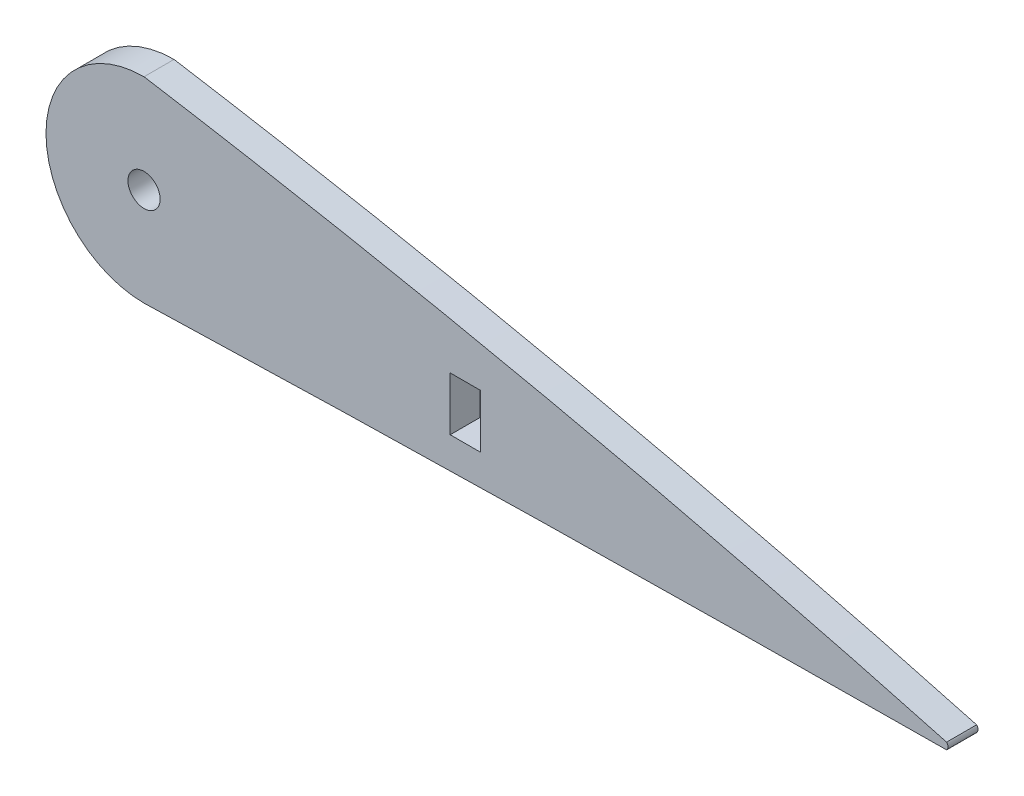
SolidWorks part; units mm, degrees
material "Фанера"
ref_plane "Front Plane" through (0, 0, 0) normal (0, 0, 1) x (1, 0, 0)
ref_plane "Top Plane" through (0, 0, 0) normal (0, 1, 0) x (1, 0, 0)
ref_plane "Right Plane" through (0, 0, 0) normal (1, 0, 0) x (0, 0, -1)
curve "Кривая5"
  spline degree 3 poles (0.048, 0.6214, 0) (0.0227, 0.3735, 0) (-0.0278, -0.1225, 0) (0.078, -0.8844, 0) (0.3497, -1.6388, 0) (0.8143, -2.3651, 0) (1.4635, -3.0393, 0) (2.291, -3.661, 0) (3.3059, -4.2358, 0) (4.5353, -4.7737, 0) (6.0297, -5.2822, 0) (7.869, -5.7653, 0) (10.1688, -6.2217, 0) (13.0754, -6.6396, 0) (16.7281, -6.993, 0) (21.19, -7.2473, 0) (26.4, -7.3766, 0) (32.1974, -7.3763, 0) (38.3978, -7.2614, 0) (44.8576, -7.0566, 0) (51.4865, -6.7865, 0) (58.231, -6.4723, 0) (65.0521, -6.1329, 0) (71.9108, -5.784, 0) (78.7714, -5.4397, 0) (85.6105, -5.111, 0) (92.4321, -4.805, 0) (99.255, -4.532, 0) (106.0974, -4.2783, 0) (112.9692, -4.0031, 0) (119.8644, -3.7232, 0) (126.7739, -3.4401, 0) (133.6816, -3.1587, 0) (140.5819, -2.8824, 0) (147.472, -2.6139, 0) (154.3526, -2.3556, 0) (161.225, -2.1094, 0) (168.0909, -1.8766, 0) (174.9516, -1.6586, 0) (181.8086, -1.4564, 0) (188.6632, -1.2704, 0) (195.5166, -1.1011, 0) (202.3695, -0.9486, 0) (209.2212, -0.8129, 0) (216.0668, -0.6936, 0) (222.8864, -0.5903, 0) (229.6176, -0.5029, 0) (236.0874, -0.4315, 0) (241.9808, -0.3765, 0) (246.559, -0.3395, 0) (249.1205, -0.3213, 0) (250, -0.315, 0) knots 0 0 0 0 0.002941 0.005884 0.009016 0.012365 0.016008 0.020037 0.024574 0.029784 0.035897 0.04324 0.052276 0.063635 0.077983 0.095698 0.11652 0.139661 0.164312 0.189919 0.216157 0.242838 0.269834 0.296993 0.324123 0.351139 0.378036 0.404946 0.431961 0.459078 0.486347 0.513641 0.540929 0.568176 0.59538 0.622543 0.649673 0.676775 0.703855 0.730919 0.757971 0.785018 0.812062 0.839103 0.866132 0.893099 0.919831 0.94581 0.969681 0.98959 1 1 1 1
curve "Кривая6"
  spline degree 3 poles (250, 0.315, 0) (249.1557, 0.545, 0) (246.7202, 1.2085, 0) (242.3913, 2.3583, 0) (236.8498, 3.7876, 0) (230.7799, 5.298, 0) (224.4559, 6.8129, 0) (218.0305, 8.2916, 0) (211.5624, 9.7197, 0) (205.0724, 11.0924, 0) (198.568, 12.4079, 0) (192.0524, 13.6653, 0) (185.5276, 14.8641, 0) (178.9953, 16.0034, 0) (172.4571, 17.0824, 0) (165.9143, 18.0998, 0) (159.3687, 19.0545, 0) (152.8218, 19.9449, 0) (146.2754, 20.7693, 0) (139.7314, 21.5257, 0) (133.1918, 22.212, 0) (126.6587, 22.8257, 0) (120.1368, 23.364, 0) (113.6286, 23.8247, 0) (107.1527, 24.2002, 0) (100.7411, 24.4984, 0) (94.4118, 24.6866, 0) (88.1559, 24.7401, 0) (81.949, 24.6588, 0) (75.7805, 24.441, 0) (69.6537, 24.0819, 0) (63.5754, 23.578, 0) (57.5552, 22.9249, 0) (51.6058, 22.1191, 0) (45.7444, 21.1566, 0) (39.9959, 20.0354, 0) (34.3979, 18.7563, 0) (29.0104, 17.3276, 0) (23.9258, 15.7719, 0) (19.2707, 14.1343, 0) (15.1791, 12.4833, 0) (11.7405, 10.8956, 0) (8.9594, 9.4296, 0) (6.7609, 8.1086, 0) (5.0337, 6.9246, 0) (3.6717, 5.8542, 0) (2.5921, 4.8713, 0) (1.7382, 3.9526, 0) (1.0699, 3.0809, 0) (0.5716, 2.2416, 0) (0.2158, 1.4308, 0) (0.1023, 0.8832, 0) (0.048, 0.6214, 0) knots 0 0 0 0 0.010162 0.029313 0.052012 0.076619 0.101948 0.127526 0.153184 0.178868 0.204558 0.230246 0.255926 0.281594 0.307246 0.332878 0.358485 0.384061 0.409603 0.435104 0.460559 0.485959 0.511303 0.536552 0.561723 0.586629 0.611085 0.635251 0.659272 0.683164 0.706922 0.730536 0.753983 0.777235 0.800246 0.822951 0.845237 0.866916 0.887662 0.906968 0.924203 0.938879 0.950932 0.960693 0.968647 0.975233 0.980795 0.985584 0.989782 0.993521 0.996902 1 1 1 1
sketch "Эскиз1" plane through (0, 0, 0) normal (0, 0, 1) x (1, 0, 0)
  line L0 (250.1305, 0) -> (250.1305, 54.8427) construction
  line L1 (0, 0) -> (0, 70.5199) construction
  line L2 (0, 0) -> (253.0634, 0) construction
  line L3 (62.5326, 62.6361) -> (62.5326, -41.5636) construction
  line L4 (142.5326, 67.9319) -> (142.5326, -57.0034) construction
  line L5 (175.0913, 63.8571) -> (175.0913, -32.3947) construction
  line L6 (32.5326, -14.3434) -> (32.5326, 29.5903) construction
  line L7 (165.9405, 18.0854) -> (165.9405, -1.9504)
  line L9 (203.6663, 6.9939) -> (206.5163, 6.9939)
  line L10 (203.6663, 6.9939) -> (203.6663, 1.9939)
  line L11 (203.6663, 1.9939) -> (206.5163, 1.9939)
  line L12 (206.5163, 6.9939) -> (206.5163, 1.9939)
  line L13 (203.6663, 6.9939) -> (206.5163, 1.9939) construction
  line L14 (203.6663, 1.9939) -> (206.5163, 6.9939) construction
  arc A0 (250, 0.315) -> (250, -0.315) centre (249.685, 0) cw
  circle A1 centre (62.5326, 8.5962) radius 8.1
  circle A2 centre (142.5326, 8.5962) radius 5.1
  circle A3 centre (32.5326, 5.4481) radius 7
  circle A5 centre (102.5326, 8.5962) radius 9.5
  arc A6 (175.0913, -1.657) -> (175.0913, 16.6448) centre (175.0913, 7.4939) cw
  circle A7 centre (175.0913, 7.4939) radius 1.5
  spline S0 degree 3 poles (-1998.9862, 52.2873) (51.3697, 19.9849) (-1.4299, 9.9734) (0.078, -0.8844) (0.3497, -1.6388) (0.8143, -2.3651) (1.4635, -3.0393) (2.291, -3.661) (3.3059, -4.2358) (4.5353, -4.7737) (6.0297, -5.2822) (7.869, -5.7653) (10.1688, -6.2217) (13.0754, -6.6396) (16.7281, -6.993) (21.19, -7.2473) (26.4, -7.3766) (32.1974, -7.3763) (38.3978, -7.2614) (44.8576, -7.0566) (51.4865, -6.7865) (58.231, -6.4723) (65.0521, -6.1329) (71.9108, -5.784) (78.7714, -5.4397) (85.6105, -5.111) (92.4321, -4.805) (99.255, -4.532) (106.0974, -4.2783) (112.9692, -4.0031) (119.8644, -3.7232) (126.7739, -3.4401) (133.6816, -3.1587) (140.5819, -2.8824) (147.472, -2.6139) (154.3526, -2.3556) (161.225, -2.1094) (168.0909, -1.8766) (174.9516, -1.6586) (181.8086, -1.4564) (188.6632, -1.2704) (195.5166, -1.1011) (202.3695, -0.9486) (211.4992, -0.7677) (220.6031, -0.6199) (229.6176, -0.5029) (236.0874, -0.4315) (241.9808, -0.3765) (412.2827, 0.9993) (580.6451, -8.1221) (733.0822, 1918.4656) knots -0.119467 -0.119467 -0.119467 -0.119467 0.002941 0.005884 0.009016 0.012365 0.016008 0.020037 0.024574 0.029784 0.035897 0.04324 0.052276 0.063635 0.077983 0.095698 0.11652 0.139661 0.164312 0.189919 0.216157 0.242838 0.269834 0.296993 0.324123 0.351139 0.378036 0.404946 0.431961 0.459078 0.486347 0.513641 0.540929 0.568176 0.59538 0.622543 0.649673 0.676775 0.703855 0.730919 0.757971 0.785018 0.812062 0.839103 0.893099 0.919831 0.94581 0.969681 0.98959 2.9616 2.9616 2.9616 2.9616 only from (0.048, 0.6214) to (250, -0.315) construction
  spline S1 degree 3 poles (1021.8633, 1838.7787) (414.3615, -64.7736) (332.0293, -21.4512) (242.3913, 2.3583) (236.8498, 3.7876) (230.7799, 5.298) (224.4559, 6.8129) (218.0305, 8.2916) (211.5624, 9.7197) (205.0724, 11.0924) (198.568, 12.4079) (192.0524, 13.6653) (185.5276, 14.8641) (178.9953, 16.0034) (172.4571, 17.0824) (165.9143, 18.0998) (159.3687, 19.0545) (152.8218, 19.9449) (146.2754, 20.7693) (139.7314, 21.5257) (133.1918, 22.212) (126.6587, 22.8257) (120.1368, 23.364) (113.6286, 23.8247) (107.1527, 24.2002) (100.7411, 24.4984) (94.4118, 24.6866) (88.1559, 24.7401) (81.949, 24.6588) (75.7805, 24.441) (69.6537, 24.0819) (63.5754, 23.578) (57.5552, 22.9249) (51.6058, 22.1191) (45.7444, 21.1566) (39.9959, 20.0354) (34.3979, 18.7563) (29.0104, 17.3276) (23.9258, 15.7719) (19.2707, 14.1343) (15.1791, 12.4833) (11.7405, 10.8956) (8.9594, 9.4296) (6.7609, 8.1086) (5.0337, 6.9246) (3.6717, 5.8542) (2.5921, 4.8713) (1.7382, 3.9526) (1.0699, 3.0809) (0.5716, 2.2416) (-4.3308, -8.9285) (41.0506, -34.7699) (-1925.2597, 540.0689) knots -1.025 -1.025 -1.025 -1.025 0.010162 0.029313 0.052012 0.076619 0.101948 0.127526 0.153184 0.178868 0.204558 0.230246 0.255926 0.281594 0.307246 0.332878 0.358485 0.384061 0.409603 0.435104 0.460559 0.485959 0.511303 0.536552 0.561723 0.586629 0.611085 0.635251 0.659272 0.683164 0.706922 0.730536 0.753983 0.777235 0.800246 0.822951 0.845237 0.866916 0.887662 0.906968 0.924203 0.938879 0.950932 0.960693 0.968647 0.975233 0.980795 0.985584 0.989782 0.993521 0.996902 1.130551 1.130551 1.130551 1.130551 only from (250, 0.315) to (0.048, 0.6214) construction
  spline S2 degree 3 poles (0.048, 0.6214) (0.0227, 0.3735) (-0.0278, -0.1225) (0.078, -0.8844) (0.3497, -1.6388) (0.8143, -2.3651) (1.4635, -3.0393) (2.291, -3.661) (3.3059, -4.2358) (4.5353, -4.7737) (6.0297, -5.2822) (7.869, -5.7653) (10.1688, -6.2217) (13.0754, -6.6396) (16.7281, -6.993) (21.19, -7.2473) (26.4, -7.3766) (32.1974, -7.3763) (38.3978, -7.2614) (44.8576, -7.0566) (51.4865, -6.7865) (58.231, -6.4723) (65.0521, -6.1329) (71.9108, -5.784) (78.7714, -5.4397) (85.6105, -5.111) (92.4321, -4.805) (99.255, -4.532) (106.0974, -4.2783) (112.9692, -4.0031) (119.8644, -3.7232) (126.7739, -3.4401) (133.6816, -3.1587) (140.5819, -2.8824) (147.472, -2.6139) (154.3526, -2.3556) (161.225, -2.1094) (168.0909, -1.8766) (174.9516, -1.6586) (181.8086, -1.4564) (188.6632, -1.2704) (195.5166, -1.1011) (202.3695, -0.9486) (211.4992, -0.7677) (220.6031, -0.6199) (229.6176, -0.5029) (236.0874, -0.4315) (241.9808, -0.3765) (246.559, -0.3395) (249.1205, -0.3213) (250, -0.315) knots 0 0 0 0 0.002941 0.005884 0.009016 0.012365 0.016008 0.020037 0.024574 0.029784 0.035897 0.04324 0.052276 0.063635 0.077983 0.095698 0.11652 0.139661 0.164312 0.189919 0.216157 0.242838 0.269834 0.296993 0.324123 0.351139 0.378036 0.404946 0.431961 0.459078 0.486347 0.513641 0.540929 0.568176 0.59538 0.622543 0.649673 0.676775 0.703855 0.730919 0.757971 0.785018 0.812062 0.839103 0.893099 0.919831 0.94581 0.969681 0.98959 1 1 1 1
  spline S3 degree 3 poles (250, 0.315) (249.1557, 0.545) (246.7202, 1.2085) (242.3913, 2.3583) (236.8498, 3.7876) (230.7799, 5.298) (224.4559, 6.8129) (218.0305, 8.2916) (211.5624, 9.7197) (205.0724, 11.0924) (198.568, 12.4079) (192.0524, 13.6653) (185.5276, 14.8641) (178.9953, 16.0034) (172.4571, 17.0824) (165.9143, 18.0998) (159.3687, 19.0545) (152.8218, 19.9449) (146.2754, 20.7693) (139.7314, 21.5257) (133.1918, 22.212) (126.6587, 22.8257) (120.1368, 23.364) (113.6286, 23.8247) (107.1527, 24.2002) (100.7411, 24.4984) (94.4118, 24.6866) (88.1559, 24.7401) (81.949, 24.6588) (75.7805, 24.441) (69.6537, 24.0819) (63.5754, 23.578) (57.5552, 22.9249) (51.6058, 22.1191) (45.7444, 21.1566) (39.9959, 20.0354) (34.3979, 18.7563) (29.0104, 17.3276) (23.9258, 15.7719) (19.2707, 14.1343) (15.1791, 12.4833) (11.7405, 10.8956) (8.9594, 9.4296) (6.7609, 8.1086) (5.0337, 6.9246) (3.6717, 5.8542) (2.5921, 4.8713) (1.7382, 3.9526) (1.0699, 3.0809) (0.5716, 2.2416) (0.2158, 1.4308) (0.1023, 0.8832) (0.048, 0.6214) knots 0 0 0 0 0.010162 0.029313 0.052012 0.076619 0.101948 0.127526 0.153184 0.178868 0.204558 0.230246 0.255926 0.281594 0.307246 0.332878 0.358485 0.384061 0.409603 0.435104 0.460559 0.485959 0.511303 0.536552 0.561723 0.586629 0.611085 0.635251 0.659272 0.683164 0.706922 0.730536 0.753983 0.777235 0.800246 0.822951 0.845237 0.866916 0.887662 0.906968 0.924203 0.938879 0.950932 0.960693 0.968647 0.975233 0.980795 0.985584 0.989782 0.993521 0.996902 1 1 1 1
  point P22 (62.5326, 23.4501)
  point P23 (62.5326, -6.2577)
  point P26 (32.5326, 18.2506)
  point P27 (32.5326, -7.3543)
  point P30 (175.0913, 16.6448)
  point P31 (175.0913, -1.657)
  point P37 (205.0913, 4.4939)
  point P43 (194.7958, 5.5542)
  point P44 (211.3694, 4.0546)
  point P47 (205.0913, 4.0546)
  point P48 (205.0913, 4.0546)
  dimension "D3" = 16.2
  dimension "D8" = 14
  dimension "D10" = 10.2
  dimension "D9" = 19
  dimension "D15" = 9.1509
  dimension "D16" = 3
  dimension "D1" = 250.1305
  dimension "D2" = 62.5326
  dimension "D4" = 80
  dimension "D5" = 75.0391
  dimension "D6" = 29.7079
  dimension "D7" = 14.8539
  dimension "D11" = 40
  dimension "D12" = 30
  dimension "D13" = 25.6049
  dimension "D14" = 12.8025
  dimension "D17" = 2.85
  dimension "D18" = 5
  dimension "D19" = 30
  dimension "D20" = 3
extrude "Бобышка-Вытянуть1" add sketch "Эскиз1" along normal mid plane 2.8 contours A0 S3 A6 S2 A7
equation "\"D2@Эскиз1\"=\"D1@Эскиз1\"/4"
equation "\"D7@Эскиз1\"=\"D6@Эскиз1\"/2"
equation "\"D5@Эскиз1\"=\"D1@Эскиз1\"*0.3"
equation "\"D14@Эскиз1\"=\"D13@Эскиз1\"/2"
equation "\"t\"= 2.85"
